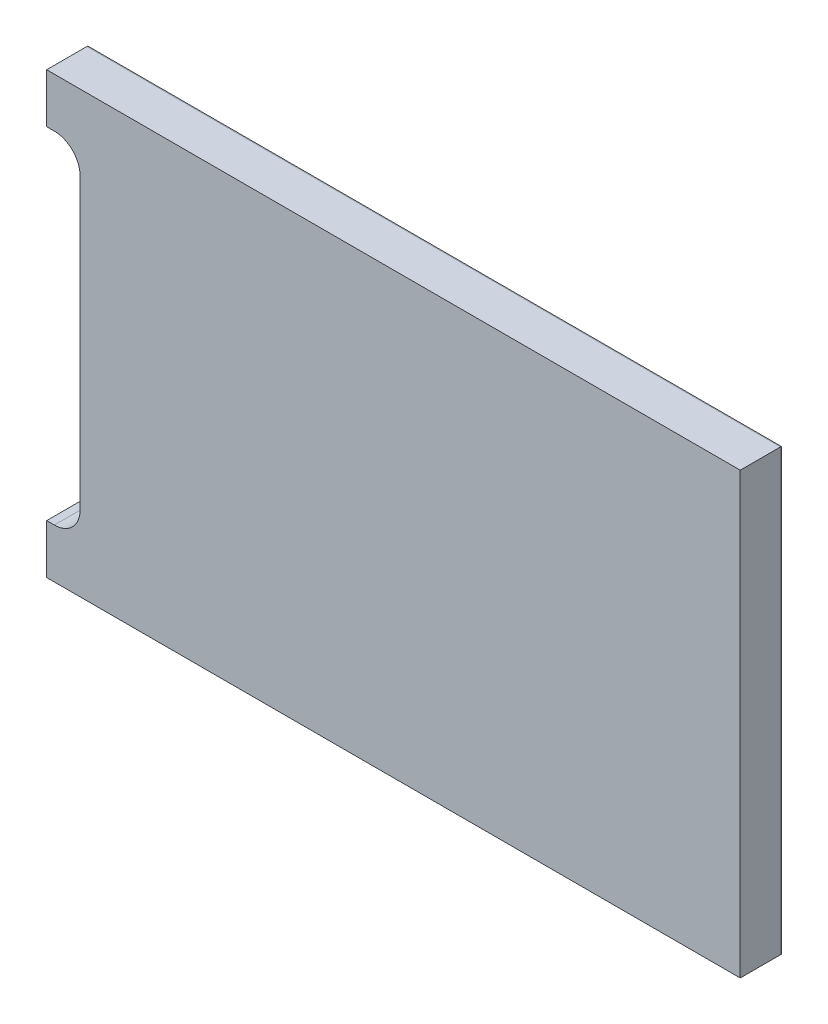
SolidWorks part; units mm, degrees
material "FR4"
ref_plane "Front Plane" through (0, 0, 0) normal (0, 0, 1) x (1, 0, 0)
ref_plane "Top Plane" through (0, 0, 0) normal (0, 1, 0) x (1, 0, 0)
ref_plane "Right Plane" through (0, 0, 0) normal (1, 0, 0) x (0, 0, -1)
sketch "Sketch1" plane through (0, 0, 0) normal (0, 0, 1) x (1, 0, 0)
  line L0 (0, 0) -> (27, 0)
  line L1 (27, 0) -> (27, 17.1204)
  line L2 (27, 17.1204) -> (0, 17.1204)
  line L3 (0, 17.1204) -> (0, 15.2)
  line L4 (1.3, 15.2) -> (1.3, 1.9204)
  line L5 (0, 1.9204) -> (1.3, 1.9204)
  line L6 (0, 15.2) -> (1.3, 15.2)
  line L7 (0, 1.9204) -> (0, 0)
extrude "Boss-Extrude1" add sketch "Sketch1" along normal blind 1.565
fillet "Fillet2" radius 1 1 edges at (1.3, 15.2, 0.7825)
fillet "Fillet3" radius 1 1 edges at (1.3, 1.9204, 0.7825)
sketch "Sketch2" plane through (0, 0, 1.565) normal (0, 0, 1) x (1, 0, 0)
sketch "Sketch4" plane through (27, 0, 0) normal (1, 0, 0) x (0, 0, -1)
  line L1 (0.035, 17.1204) -> (0.035, 0)
  line L2 (0.035, 0) -> (0.07, 0)
  line L3 (0.07, 0) -> (0.07, 17.1204)
  line L4 (0.07, 17.1204) -> (0.035, 17.1204)
  point P3 (0, 0)
  point P8 (0, 0)
  point P9 (0, 0)
extrude "Boss-Extrude2" add sketch "Sketch4" against normal blind 27 separate body
sketch "Sketch5" plane through (0, 0, -0.035) normal (0, 0, 1) x (1, 0, 0)
  line L0 (1.3, 2.9204) -> (1.3, 14.2)
  line L1 (0, 15.2) -> (0.3, 15.2)
  line L2 (0, 15.2) -> (0, 1.9204)
  line L3 (0, 1.9204) -> (0, 0) construction
  line L4 (0, 17.1204) -> (0, 0) construction
  line L6 (0, 1.9204) -> (0.3, 1.9204)
  arc A0 (1.3, 14.2) -> (0.3, 15.2) centre (0.3, 14.2) ccw
  arc A1 (1.3, 2.9204) -> (0.3, 1.9204) centre (0.3, 2.9204) cw
extrude "Cut-Extrude2" cut sketch "Sketch5" against normal blind 27
mirror "Mirror1" about plane through (0, 17.1204, -0.035) normal (0, 0, 1) of bodies 103
delete or keep bodies "Body-Delete/Keep 1" type delete bodies bodies 103
